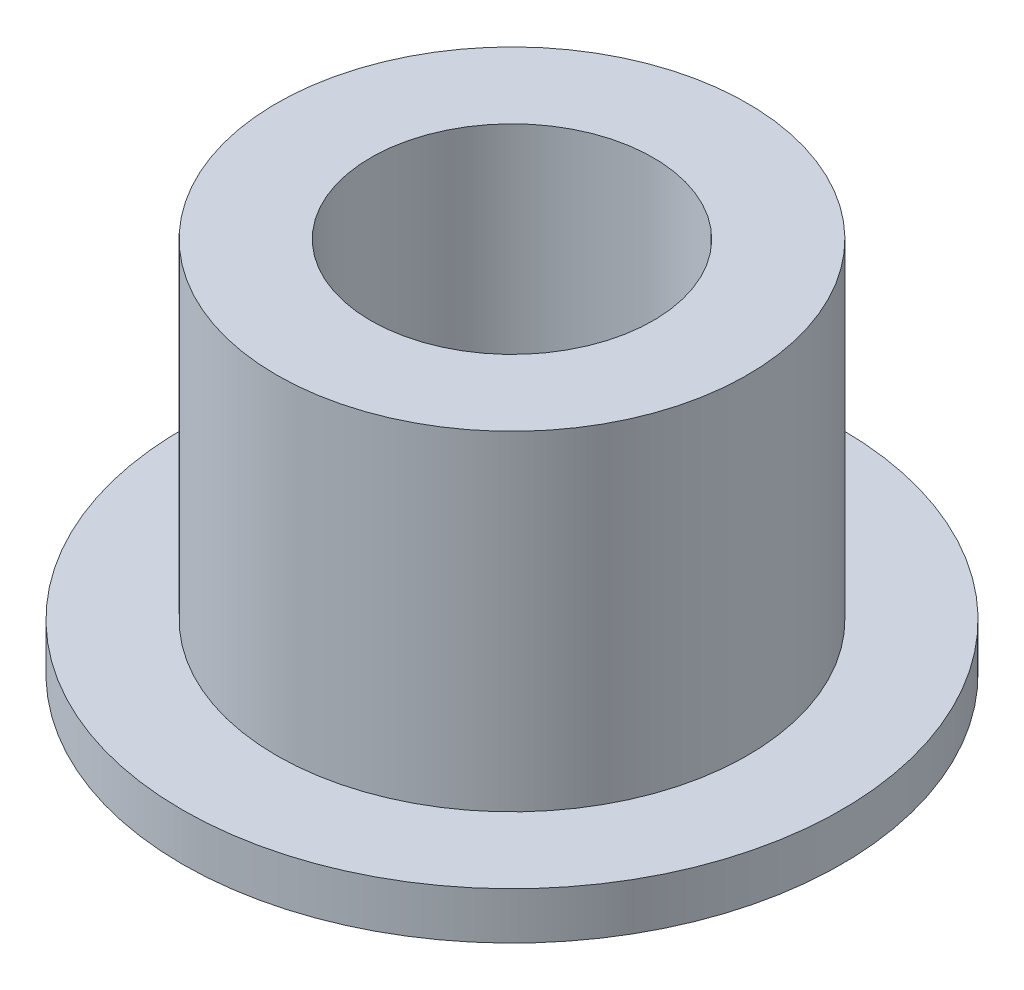
SolidWorks part; units mm, degrees
material "Tin Bearing Bronze"
ref_plane "Front Plane" through (0, 0, 0) normal (0, 0, 1) x (1, 0, 0)
ref_plane "Top Plane" through (0, 0, 0) normal (0, 1, 0) x (1, 0, 0)
ref_plane "Right Plane" through (0, 0, 0) normal (1, 0, 0) x (0, 0, -1)
sketch "Sketch1" plane through (0, 0, 0) normal (0, 1, 0) x (1, 0, 0)
  circle A0 centre (0, 0) radius 11.1125
  circle A1 centre (0, 0) radius 4.7625
  dimension "D1" = 22.225
  dimension "D2" = 9.525
extrude "Boss-Extrude1" add sketch "Sketch1" along normal blind 1.5875
sketch "Sketch2" plane through (0, 1.5875, 0) normal (0, 1, 0) x (1, 0, 0)
  circle A0 centre (0, 0) radius 4.7625
  circle A1 centre (0, 0) radius 7.9375
  dimension "D1" = 15.875
extrude "Boss-Extrude2" add sketch "Sketch2" along normal blind 11.1125
